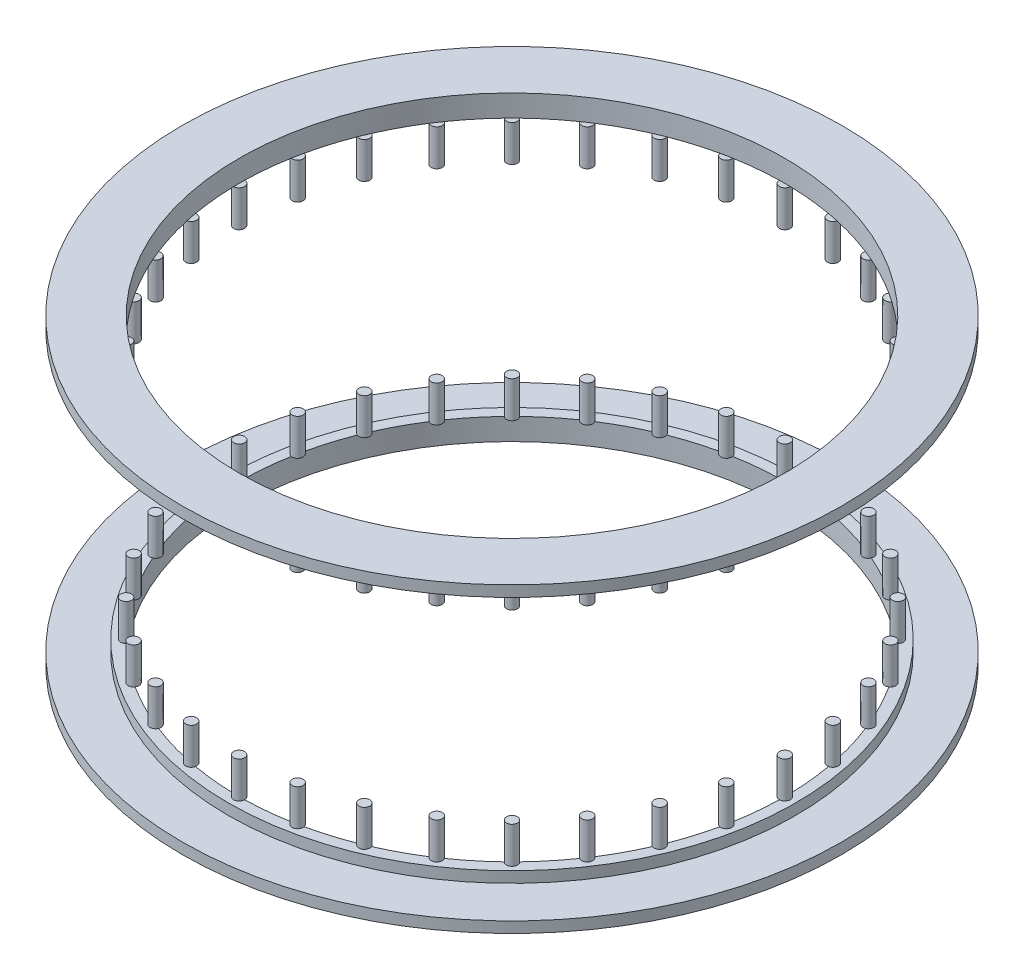
SolidWorks part; units mm, degrees
material "1023 Carbon Steel Sheet (SS)"
ref_plane "Front Plane" through (0, 0, 0) normal (0, 0, 1) x (1, 0, 0)
ref_plane "Top Plane" through (0, 0, 0) normal (0, 1, 0) x (1, 0, 0)
ref_plane "Right Plane" through (0, 0, 0) normal (1, 0, 0) x (0, 0, -1)
sketch "Sketch1" plane through (0, 0, 0) normal (1, 0, 0) x (0, 0, -1)
  line L0 (0, 380.5112) -> (0, -292.3323) construction
  line L20 (-375, 207.5) -> (-453.1959, 207.5)
  line L22 (0, 0) -> (-439.4387, 0) construction
  line L23 (-507.5, 106.25) -> (0, 106.25) construction
  line L35 (-390, 192.5) -> (-453.1959, 192.5)
  line L38 (-375, 207.5) -> (-375, 177.5)
  line L50 (-375, 177.5) -> (-390, 177.5)
  line L51 (-390, 177.5) -> (-390, 192.5)
  line L52 (-390, -177.5) -> (-390, -192.5)
  line L53 (-375, -177.5) -> (-390, -177.5)
  line L54 (-375, -207.5) -> (-375, -177.5)
  line L55 (-375, -207.5) -> (-453.1959, -207.5)
  line L56 (-390, -192.5) -> (-453.1959, -192.5)
  line L62 (-453.1959, -192.5) -> (-453.1959, -207.5)
  line L63 (-453.1959, 192.5) -> (-453.1959, 207.5)
  point P12 (-438.8978, 0)
  point P30 (-537.5, 0)
  dimension "D1" = 750
  dimension "D4" = 15
  dimension "D5" = 415
  dimension "D6" = 15
  dimension "D7" = 15
revolve "Revolve1" add sketch "Sketch1" angle 360 about L0
sketch "Sketch2" plane through (0, -177.5, 0) normal (0, 1, 0) x (1, 0, 0)
  circle A0 centre (0, 375) radius 7.5
  circle A1 centre (0, 0) radius 375 construction
  circle A2 centre (73.1589, 367.7945) radius 7.5
  circle A3 centre (143.5063, 346.4548) radius 7.5
  circle A4 centre (208.3388, 311.8011) radius 7.5
  circle A5 centre (265.165, 265.165) radius 7.5
  circle A6 centre (311.8011, 208.3388) radius 7.5
  circle A7 centre (346.4548, 143.5063) radius 7.5
  circle A8 centre (367.7945, 73.1589) radius 7.5
  circle A9 centre (375, 0) radius 7.5
  circle A10 centre (367.7945, -73.1589) radius 7.5
  circle A11 centre (346.4548, -143.5063) radius 7.5
  circle A12 centre (311.8011, -208.3388) radius 7.5
  circle A13 centre (265.165, -265.165) radius 7.5
  circle A14 centre (208.3388, -311.8011) radius 7.5
  circle A15 centre (143.5063, -346.4548) radius 7.5
  circle A16 centre (73.1589, -367.7945) radius 7.5
  circle A17 centre (0, -375) radius 7.5
  circle A18 centre (-73.1589, -367.7945) radius 7.5
  circle A19 centre (-143.5063, -346.4548) radius 7.5
  circle A20 centre (-208.3388, -311.8011) radius 7.5
  circle A21 centre (-265.165, -265.165) radius 7.5
  circle A22 centre (-311.8011, -208.3388) radius 7.5
  circle A23 centre (-346.4548, -143.5063) radius 7.5
  circle A24 centre (-367.7945, -73.1589) radius 7.5
  circle A25 centre (-375, 0) radius 7.5
  circle A26 centre (-367.7945, 73.1589) radius 7.5
  circle A27 centre (-346.4548, 143.5063) radius 7.5
  circle A28 centre (-311.8011, 208.3388) radius 7.5
  circle A29 centre (-265.165, 265.165) radius 7.5
  circle A30 centre (-208.3388, 311.8011) radius 7.5
  circle A31 centre (-143.5063, 346.4548) radius 7.5
  circle A32 centre (-73.1589, 367.7945) radius 7.5
  circle A33 centre (0, 0) radius 350 construction
  point P69 (0, 0)
  dimension "D1" = 15
  dimension "D2" = 32
extrude "Boss-Extrude1" add sketch "Sketch2" along normal blind 50
ref_plane "Plane1" through (0, 0, 0) normal (0, -1, 0) x (-1, 0, 0)
mirror "Mirror1" about plane through (0, 0, 0) normal (0, -1, 0) of "Boss-Extrude1"
